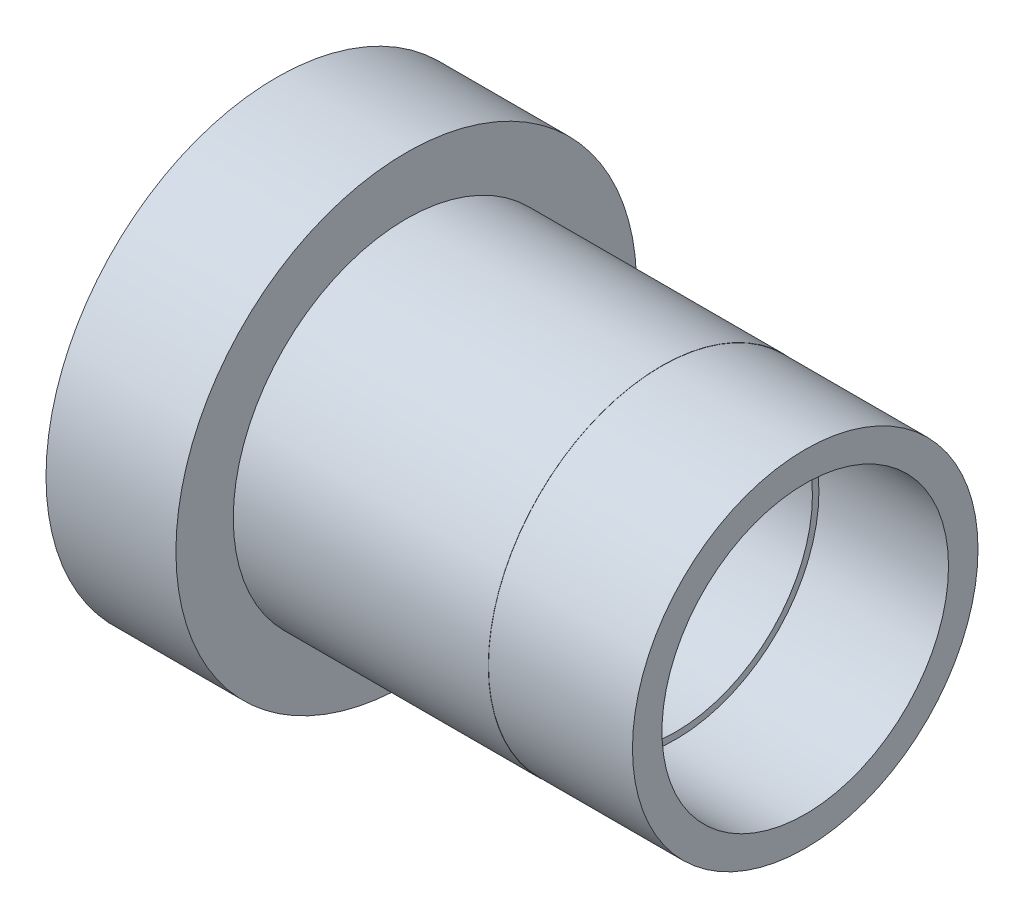
SolidWorks part; units mm, degrees
material "6061-T6 (SS)"
ref_plane "Front Plane" through (0, 0, 0) normal (0, 0, 1) x (1, 0, 0)
ref_plane "Top Plane" through (0, 0, 0) normal (0, 1, 0) x (1, 0, 0)
ref_plane "Right Plane" through (0, 0, 0) normal (1, 0, 0) x (0, 0, -1)
sketch "Sketch1" plane through (0, 0, 0) normal (0, 0, 1) x (1, 0, 0)
  line L2 (0, 0) -> (0, 4.7625)
  line L5 (-10.9982, 6.35) -> (-14.5796, 6.35)
  line L6 (-14.5796, 6.35) -> (-14.5796, 0)
  line L7 (-14.5796, 0) -> (0, 0)
  line L8 (-3.9688, 4.7625) -> (-3.9688, 4.7688)
  line L9 (-3.9688, 4.7688) -> (-10.9982, 4.7688)
  line L10 (-3.9688, 4.7625) -> (0, 4.7625)
  line L11 (-10.9982, 4.7688) -> (-10.9982, 6.35)
  dimension "D1" = 10.9982
  dimension "D2" = 14.5796
  dimension "D3" = 4.7625
  dimension "D4" = 6.35
  dimension "D5" = 4.7688
  dimension "D6" = 3.9688
revolve "Revolve1" add sketch "Sketch1" angle 360 about L7
sketch "Sketch2" plane through (0, 0, 0) normal (1, 0, 0) x (0, 0, -1)
  circle A0 centre (0, 0) radius 3.9497
  dimension "D1" = 7.8994
extrude "Cut-Extrude1" cut sketch "Sketch2" against normal blind 3.5719
sketch "Sketch3" plane through (-14.5796, 0, 0) normal (-1, 0, 0) x (0, 0, 1)
  circle A0 centre (0, 0) radius 3.7703
  dimension "D1" = 7.5406
extrude "Cut-Extrude2" cut sketch "Sketch3" against normal through all
sketch "Sketch4" plane through (-14.5796, 0, 0) normal (-1, 0, 0) x (0, 0, 1)
  circle A0 centre (0, 0) radius 3.9497
  dimension "D1" = 7.8994
extrude "Cut-Extrude3" cut sketch "Sketch4" against normal blind 3.5719
